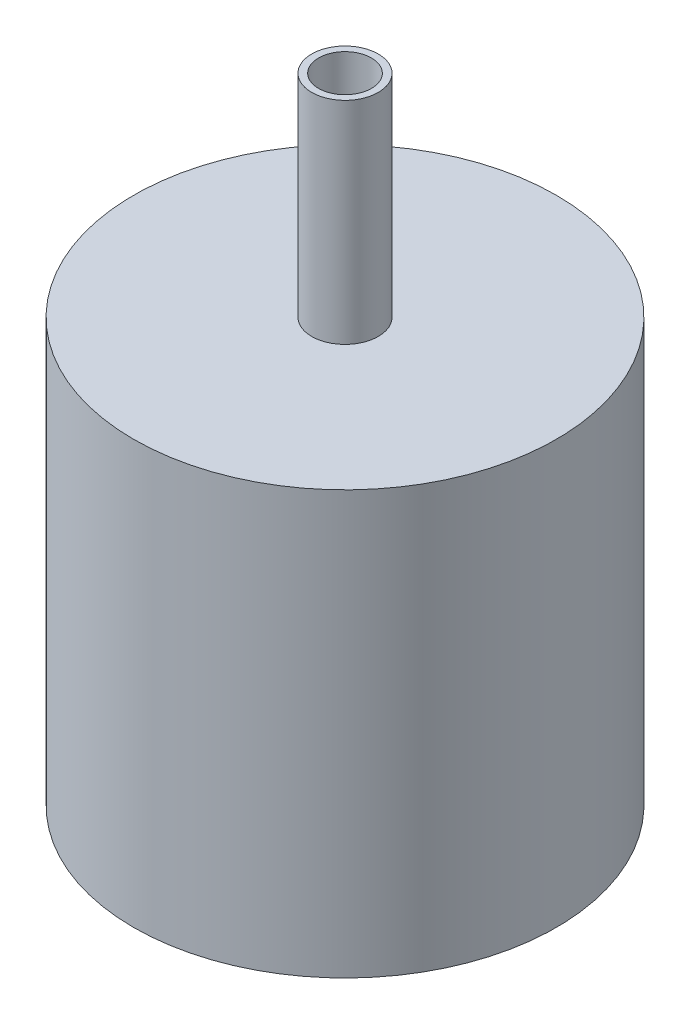
SolidWorks part; units mm, degrees
material "Delrin 2700 NC010, Low Viscosity Acetal Copolymer (SS)"
ref_plane "Front Plane" through (0, 0, 0) normal (0, 0, 1) x (1, 0, 0)
ref_plane "Top Plane" through (0, 0, 0) normal (0, 1, 0) x (1, 0, 0)
ref_plane "Right Plane" through (0, 0, 0) normal (1, 0, 0) x (0, 0, -1)
sketch "Sketch1" plane through (0, 0, 0) normal (0, 1, 0) x (1, 0, 0)
  circle A0 centre (0, 0) radius 12.7
  dimension "D1" = 25.4
extrude "Boss-Extrude1" add sketch "Sketch1" along normal blind 25.4
sketch "Sketch2" plane through (0, 0, 0) normal (0, 1, 0) x (1, 0, 0)
  circle A0 centre (0, 0) radius 7.9375
  dimension "D1" = 15.875
extrude "Cut-Extrude1" cut sketch "Sketch2" along normal blind 3.175
sketch "Sketch12" plane through (0, 25.4, 0) normal (0, 1, 0) x (1, 0, 0)
  circle A0 centre (0, 0) radius 2
  dimension "D1" = 4
extrude "Boss-Extrude3" add sketch "Sketch12" along normal blind 12.7
hole_wizard "1/8 (0.125) Diameter Hole1" positions "Sketch9" profile "Sketch11" hole size "1/8" standard "ANSI Inch" end condition through all
sketch "Sketch9" plane through (0, 3.175, 0) normal (0, -1, 0) x (-1, 0, 0)
  point P0 (0, 0)
sketch "Sketch11" plane through (0, 3.175, 0) normal (1, 0, 0) x (0, 0, -1)
  line L0 (0, 0) -> (0, 34.925)
  line L1 (0, 34.925) -> (1.5875, 34.925)
  line L2 (1.5875, 34.925) -> (1.5875, 0)
  line L5 (1.5875, 0) -> (0, 0)
  line L11 (0, -6.35) -> (0, 107.95) construction
  dimension "Thru Hole Dia." = 3.175
  dimension "Thru Hole Depth" = 34.925
